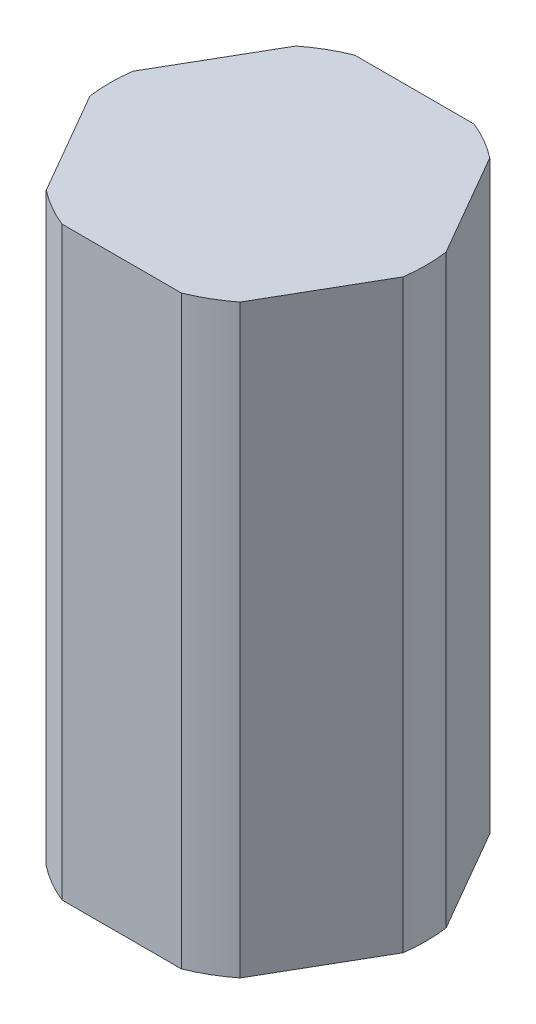
SolidWorks part; units mm, degrees
ref_plane "Front" through (0, 0, 0) normal (0, 0, 1) x (1, 0, 0)
ref_plane "Top" through (0, 0, 0) normal (0, 1, 0) x (1, 0, 0)
ref_plane "Right" through (0, 0, 0) normal (1, 0, 0) x (0, 0, -1)
sketch "Sketch1" plane through (0, 0, 0) normal (0, 1, 0) x (1, 0, 0)
  line L1 (2.8868, 0) -> (1.4434, 2.5)
  line L2 (1.4434, 2.5) -> (-1.4434, 2.5)
  line L3 (-1.4434, 2.5) -> (-2.8868, 0)
  line L4 (-2.8868, 0) -> (-1.4434, -2.5)
  line L5 (-1.4434, -2.5) -> (1.4434, -2.5)
  line L6 (1.4434, -2.5) -> (2.8868, 0)
  circle A0 centre (0, 0) radius 2.5 construction
  circle A1 centre (0, 0) radius 2.7
extrude "Boss-Extrude1" add sketch "Sketch1" along normal blind 10 contours L5 A1 L6 L1 L2 L3 L4
